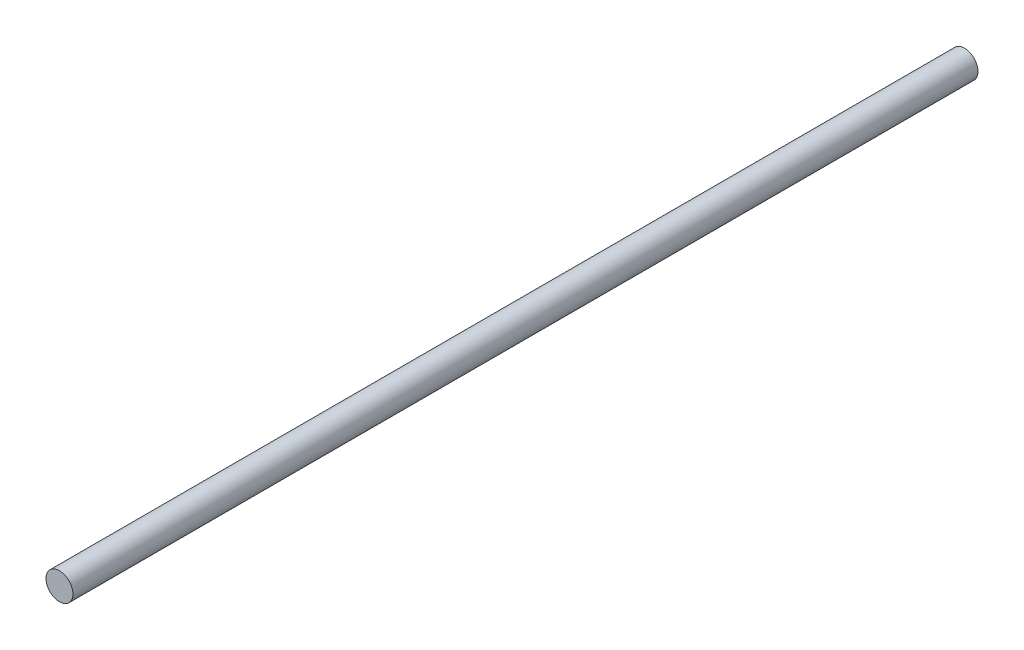
SolidWorks part; units mm, degrees
ref_plane "Front Plane" through (0, 0, 0) normal (0, 0, 1) x (1, 0, 0)
ref_plane "Top Plane" through (0, 0, 0) normal (0, 1, 0) x (1, 0, 0)
ref_plane "Right Plane" through (0, 0, 0) normal (1, 0, 0) x (0, 0, -1)
sketch "Sketch1" plane through (0, 0, 0) normal (0, 0, 1) x (1, 0, 0)
  circle A0 centre (0, 0) radius 3.175
  dimension "D1" = 6.35
extrude "Boss-Extrude1" add sketch "Sketch1" against normal blind 213.106
